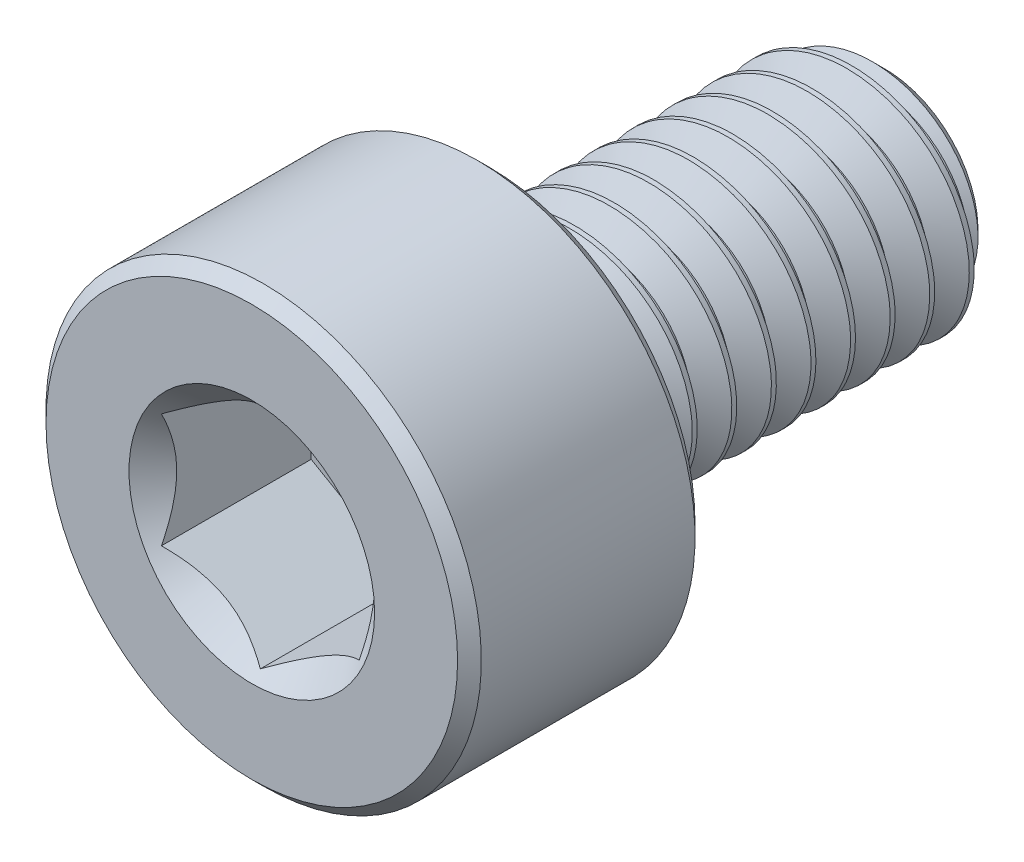
SolidWorks part; units mm, degrees
ref_plane "Front Plane" through (0, 0, 0) normal (0, 0, 1) x (1, 0, 0)
ref_plane "Top Plane" through (0, 0, 0) normal (0, 1, 0) x (1, 0, 0)
ref_plane "Right Plane" through (0, 0, 0) normal (1, 0, 0) x (0, 0, -1)
sketch "Sketch1" plane through (0, 0, 0) normal (1, 0, 0) x (0, 0, -1)
  line L0 (-4, 0) -> (4, 0) construction
  line L1 (4, 0) -> (4, 1.1752) construction
  line L2 (4, 1.1752) -> (3.6752, 1.5) construction
  line L3 (3.6752, 1.5) -> (3.625, 1.5) construction
  line L4 (3.625, 1.5) -> (-1, 1.5) construction
  line L5 (-1, 1.5) -> (-1, 2.75) construction
  line L6 (-1, 2.75) -> (-4, 2.75) construction
  line L7 (-4, 2.75) -> (-4, 0) construction
  line L8 (4, 1.1752) -> (4, 1.5) construction
  line L9 (3.9687, 1.5541) -> (4.2187, 1.1211) construction
  line L10 (4.2187, 1.1211) -> (4.4687, 1.5541) construction
  line L11 (4.4687, 1.5541) -> (3.9687, 1.5541) construction
  line L12 (4.2187, 1.5541) -> (4.2188, 1.5) construction
  line L13 (4.2187, 1.1211) -> (4.2187, 1.1752) construction
  line L14 (4.1875, 1.1752) -> (4.25, 1.1752) construction
  line L15 (4, 1.5) -> (4.4375, 1.5) construction
  line L16 (3.9844, 1.5271) -> (4.4531, 1.5271) construction
  line L17 (4, 0) -> (4, -1.5) construction
  line L18 (-1.15, 2.75) -> (-1, 2.6) construction
  line L19 (-3.85, 2.75) -> (-4, 2.6) construction
  line L20 (-1, 1.5) -> (-1, 0) construction
  line L21 (-1, 0.75) -> (0.6667, 0.75) construction
  line L22 (0.6667, 0.75) -> (2.3333, 0.75) construction
  line L23 (2.3333, 0.75) -> (4, 0.75) construction
  line L24 (0.6667, 0.75) -> (0.6667, 1.5) construction
  line L25 (0.6667, 1.5) -> (0.6667, 2.75) construction
  line L26 (2.3333, 0.75) -> (2.3333, 2.75) construction
  point P0 (-4, 1.25)
  point P3 (2.75, 1.5)
  point P4 (0, 0)
  point P18 (2.3333, 1.5)
  point P22 (4.2187, 1.1752)
  point P24 (3.625, 1.5)
  point P25 (4.2188, 1.5)
  point P28 (4.2188, 1.5271)
  point P29 (2.75, -1.5)
  point P30 (0.6667, 1.5)
  point P31 (-2.5, 2.75)
  point P37 (-1.525, 2.75)
  point P38 (-3.775, 2.75)
  point P45 (0.6667, 0.75)
  point P46 (2.3333, 0.75)
  dimension "D2" = 0.0625
  dimension "D7" = 0.15
  dimension "D8" = 0.15
  dimension "D9" = 0.15
  dimension "D10" = 0.075
  dimension "D11" = 0.375
  dimension "Drive Size" = 2.5
  dimension "Head Diameter" = 5.5
  dimension "Head Height" = 3
  dimension "Thread Pitch" = 0.5
  dimension "Thread Size" = 3
  dimension "Length" = 5
  dimension "D12" = 0.375
  dimension "D4" = 1.25
  dimension "D3" = 45
sketch "Sketch2" plane through (0, 0, 0) normal (1, 0, 0) x (0, 0, -1)
  line L0 (-4, 0) -> (-4, 2.6)
  line L1 (-3.85, 2.75) -> (-1.15, 2.75)
  line L2 (-1, 2.6) -> (-1, 1.65)
  line L4 (3.6752, 1.5) -> (4, 1.1752)
  line L5 (4, 1.1752) -> (4, 0)
  line L6 (-1, 2.75) -> (-4, 2.75) construction
  line L7 (4, 0) -> (-4, 0)
  line L8 (-3.85, 2.75) -> (-4, 2.6) construction
  line L10 (-3.85, 2.75) -> (-4, 2.6)
  line L14 (-1.15, 2.75) -> (-1, 2.6) construction
  line L16 (-1.15, 2.75) -> (-1, 2.6)
  line L17 (-1, 1.5) -> (-1, 2.75) construction
  line L19 (-0.85, 1.5) -> (3.6752, 1.5)
  line L20 (3.625, 1.5) -> (-1, 1.5) construction
  arc A1 (-1, 1.65) -> (-0.85, 1.5) centre (-0.85, 1.65) ccw
revolve "Revolve1" add sketch "Sketch2" angle 360 about L7
sketch "Sketch3" plane through (0, 0, 4) normal (0, 0, 1) x (1, 0, 0)
  line L1 (1.25, -0.7217) -> (1.25, 0.7217)
  line L2 (1.25, 0.7217) -> (0, 1.4434)
  line L3 (0, 1.4434) -> (-1.25, 0.7217)
  line L4 (-1.25, 0.7217) -> (-1.25, -0.7217)
  line L5 (-1.25, -0.7217) -> (0, -1.4434)
  line L6 (0, -1.4434) -> (1.25, -0.7217)
  circle A0 centre (0, 0) radius 1.25 construction
  circle A1 centre (0, 0) radius 2.75 construction
  circle A2 centre (0, 0) radius 2.75 construction
  circle A3 centre (0, 0) radius 1.4434 construction
  point P13 (0, 0)
  dimension "D1" = 2.8868
extrude "Cut-Extrude1" cut sketch "Sketch3" against normal offset from surface (2 mm away) 1 up to face at (0, 2.6, 1)
sketch "Sketch4" plane through (0, 0, 4) normal (0, 0, 1) x (1, 0, 0)
  circle A0 centre (0, 0) radius 1.5516
  dimension "D1" = 3.1033
extrude "Cut-Extrude2" cut sketch "Sketch4" against normal up to vertex (1.5 mm away) draft 45 up to point (0, 2.75, 2.5)
sketch "Sketch11" plane through (0, 0, 0) normal (1, 0, 0) x (0, 0, -1)
  line L0 (-4, 0) -> (4, 0) construction
  line L1 (-4, 0) -> (4, 0) construction
  line L2 (-0.0625, 0) -> (-0.0625, 1.5) construction
  line L3 (3.625, 1.5) -> (-1, 1.5) construction
  line L4 (3.0625, 0) -> (3.0625, 1.5) construction
  line L6 (4, 1.1752) -> (4, 1.5) construction
  point P2 (-0.0625, 0)
  point P3 (3.0625, 0)
  dimension "D1" = 0.9375
  dimension "D2" = 0.9375
sketch "Sketch6" plane through (0, 0, -4) normal (0, 0, -1) x (-1, 0, 0)
  circle A0 centre (0, 0) radius 1.5
curve "Helix/Spiral1" pitch 0.5 height 5.5 turns 11
sketch "Sketch10" plane through (0, 0, 0) normal (1, 0, 0) x (0, 0, -1)
  line L0 (-0.85, -2.75) -> (-0.85, 2.75)
  line L5 (-4, 0) -> (4, 0) construction
  line L6 (-0.85, 1.5) -> (-0.85, -1.5) construction
  point P3 (-0.85, 0)
split "Split1" trim tools "Sketch10" bodies to split 106 resulting bodies 114 115
sketch "Sketch7" plane through (0, 0, 0) normal (1, 0, 0) x (0, 0, -1)
  line L0 (3.9844, 1.5271) -> (4.4531, 1.5271)
  line L1 (4.4531, 1.5271) -> (4.25, 1.1752)
  line L2 (4.25, 1.1752) -> (4.1875, 1.1752)
  line L3 (4.1875, 1.1752) -> (3.9844, 1.5271)
sweep "Cut-Sweep1" cut profiles "Sketch7" path "Helix/Spiral1"
sketch "Sketch8" plane through (0, 0, 0) normal (1, 0, 0) x (0, 0, -1)
  line L0 (-1, 0) -> (-1, 1.5)
  line L1 (-0.85, -1.5) -> (-0.85, 1.5) construction
  line L2 (-1, 1.5) -> (-0.85, 1.5)
  line L4 (-0.85, 1.5) -> (0.016, 0)
  line L5 (0.016, 0) -> (-1, 0)
  line L6 (3.625, 1.5) -> (-1, 1.5) construction
  line L7 (-4, 0) -> (4, 0) construction
  dimension "D1" = 60
revolve "Revolve2" add sketch "Sketch8" angle 360 about L5
equation "\"D2@Sketch1\" = \"Thread Pitch@Sketch1\" / 8"
equation "\"D4@Helix/Spiral1\" = \"Thread Pitch@Sketch1\""
equation "\"D7@Sketch1\" = \"Head Height@Sketch1\" * .05"
equation "\"D8@Sketch1\"=\"D7@Sketch1\""
equation "\"D9@Sketch1\"=\"D7@Sketch1\""
equation "\"D10@Sketch1\"=\"D7@Sketch1\"/2"
equation "\"D11@Sketch1\"=\"D10@Sketch1\"*5"
equation "\"D4@Sketch1\"=\"Thread Pitch@Sketch1\"*2.5"
equation "\"D12@Sketch1\"=\"Thread Pitch@Sketch1\"*.75"
equation "\"D3@Helix/Spiral1\"=\"Length@Sketch1\"+\"Thread Pitch@Sketch1\""
equation "\"D3@Sketch2\"=\"Thread Size@Sketch1\"*0.05"
equation "\"D1@Sketch11\"=\"Length@Sketch1\"*0.1875"
equation "\"D2@Sketch11\"=\"D1@Sketch11\""
equation "\"D1@Sketch4\"=\"D1@Sketch3\"*1.075"
